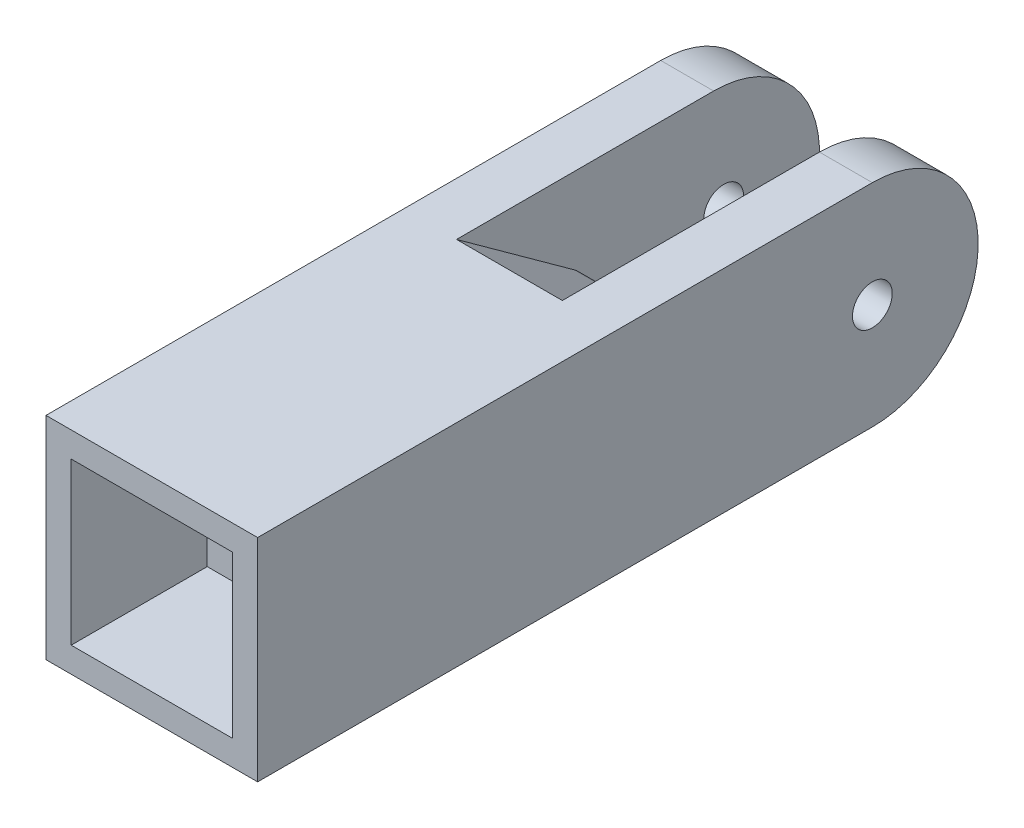
SolidWorks part; units mm, degrees
ref_plane "Front Plane" through (0, 0, 0) normal (0, 0, 1) x (1, 0, 0)
ref_plane "Top Plane" through (0, 0, 0) normal (0, 1, 0) x (1, 0, 0)
ref_plane "Right Plane" through (0, 0, 0) normal (1, 0, 0) x (0, 0, -1)
sketch "Sketch2" plane through (0, 0, 0) normal (0, 0, 1) x (1, 0, 0)
  line L1 (-21, 21) -> (21, 21)
  line L2 (-21, 21) -> (-21, -21)
  line L3 (-21, -21) -> (21, -21)
  line L4 (21, 21) -> (21, -21)
  line L5 (-21, 21) -> (21, -21) construction
  line L6 (-21, -21) -> (21, 21) construction
  point P0 (0, 0)
  dimension "D1" = 42
  dimension "D2" = 42
extrude "Boss-Extrude1" add sketch "Sketch2" along normal blind 100
ref_plane "Plane1" through (0, 0, 0) normal (0, 0, -1) x (-1, 0, 0)
sketch "Sketch3" plane through (0, 0, 0) normal (0, 0, -1) x (-1, 0, 0)
  line L0 (-21, 21) -> (21, 21) construction
  line L1 (21, -21) -> (10.5, -21)
  line L2 (21, -21) -> (21, 21)
  line L3 (21, 21) -> (10.5, 21)
  line L4 (10.5, -21) -> (10.5, 21)
  line L6 (-21, -21) -> (-10.5, -21)
  line L7 (-21, -21) -> (-21, 21)
  line L8 (-21, 21) -> (-10.5, 21)
  line L9 (-10.5, -21) -> (-10.5, 21)
  dimension "D1" = 10.5
  dimension "D2" = 10.5
extrude "Boss-Extrude2" add sketch "Sketch3" along normal blind 22
ref_plane "Plane2" through (-21, 0, 0) normal (-1, 0, 0) x (0, 0, 1)
sketch "Sketch4" plane through (-21, 0, 0) normal (-1, 0, 0) x (0, 0, 1)
  line L0 (-22, -21) -> (-22, 21)
  arc A0 (-22, -21) -> (-22, 21) centre (-22, 0) cw
  dimension "D1" = 21
extrude "Boss-Extrude3" add sketch "Sketch4" against normal blind 10.5
ref_plane "Plane3" through (21, 0, 0) normal (1, 0, 0) x (0, 0, -1)
sketch "Sketch5" plane through (21, 0, 0) normal (1, 0, 0) x (0, 0, -1)
  line L0 (22, 21) -> (22, -21)
  arc A0 (22, 21) -> (22, -21) centre (22, 0) cw
  dimension "D1" = 21
extrude "Boss-Extrude4" add sketch "Sketch5" against normal blind 10.5
ref_plane "Plane4" through (0, 0, 100) normal (0, 0, 1) x (1, 0, 0)
sketch "Sketch6" plane through (0, 0, 100) normal (0, 0, 1) x (1, 0, 0)
  line L0 (21, 21) -> (-21, 21) construction
  line L1 (-16, 16) -> (16, 16)
  line L2 (-16, 16) -> (-16, -16)
  line L3 (-16, -16) -> (16, -16)
  line L4 (16, 16) -> (16, -16)
  line L5 (-16, 16) -> (16, -16) construction
  line L6 (-16, -16) -> (16, 16) construction
  line L7 (21, -21) -> (21, 21) construction
  point P0 (0, 0)
  dimension "D1" = 5
  dimension "D2" = 5
extrude "Cut-Extrude1" cut sketch "Sketch6" against normal blind 27
ref_plane "Plane5" through (10.5, 0, 0) normal (-1, 0, 0) x (0, 0, 1)
sketch "Sketch7" plane through (10.5, 0, 0) normal (-1, 0, 0) x (0, 0, 1)
  line L0 (0, -21) -> (0, 21) construction
  circle A0 centre (-22, 0) radius 3.95
  dimension "D2" = 7.9
  dimension "D1" = 22
extrude "Cut-Extrude2" cut sketch "Sketch7" against normal through all
ref_plane "Plane6" through (-10.5, 0, 0) normal (1, 0, 0) x (0, 0, -1)
sketch "Sketch9" plane through (-10.5, 0, 0) normal (1, 0, 0) x (0, 0, -1)
  line L0 (0, 21) -> (0, -21) construction
  circle A0 centre (24, 0) radius 3.95
  dimension "D2" = 7.9
  dimension "D1" = 24
extrude "Cut-Extrude3" cut sketch "Sketch9" against normal through all
ref_plane "Plane9" through (10.5, 0, 0) normal (-1, 0, 0) x (0, 0, 1)
sketch "Sketch11" plane through (10.5, 0, 0) normal (-1, 0, 0) x (0, 0, 1)
  line L0 (0, 0) -> (0, 21)
  line L1 (0, 0) -> (0, -21)
  line L2 (0, -21) -> (29.0252, -21)
  line L3 (29.0252, -21) -> (0, 0)
  line L4 (0, -21) -> (0, 21) construction
  line L5 (0, 21) -> (29.0252, 21) construction
  line L6 (29.0252, 21) -> (0, 0) construction
  line L7 (0, 0) -> (0, 21)
  line L8 (0, 0) -> (29.0252, 21)
  line L9 (29.0252, 21) -> (0, 21)
  line M5 (0, -21) -> (0, 21)
extrude "Cut-Extrude4" cut sketch "Sketch11" along normal blind 21 contours L8 L9 M5 | L2 L3 M5
fillet "Fillet1" radius 5 1 edges at (0, 0, 0)
